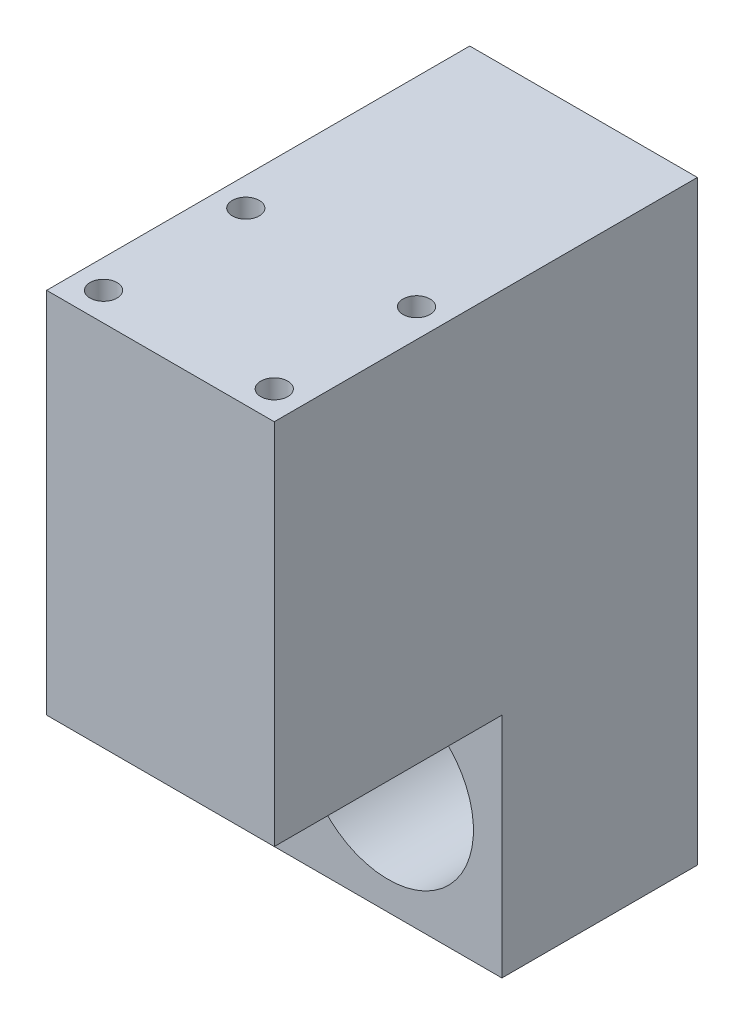
SolidWorks part; units mm, degrees
ref_plane "Front Plane" through (0, 0, 0) normal (0, 0, 1) x (1, 0, 0)
ref_plane "Top Plane" through (0, 0, 0) normal (0, 1, 0) x (1, 0, 0)
ref_plane "Right Plane" through (0, 0, 0) normal (1, 0, 0) x (0, 0, -1)
sketch "Sketch1" plane through (0, 0, 0) normal (0, 1, 0) x (1, 0, 0)
  line L1 (-18.3087, -9.8557) -> (-10.3087, -9.8557)
  line L2 (-18.3087, -9.8557) -> (-18.3087, -2.9857)
  line L3 (-18.3087, -2.9857) -> (-10.3087, -2.9857)
  line L4 (-10.3087, -9.8557) -> (-10.3087, -2.9857)
  dimension "D1" = 6.87
  dimension "D2" = 8
extrude "Boss-Extrude3" add sketch "Sketch1" along normal blind 8
sketch "Sketch2" plane through (0, 8, 0) normal (0, 1, 0) x (1, 0, 0)
  line L1 (-18.3087, -2.9857) -> (-10.3087, -2.9857)
  line L2 (-18.3087, -2.9857) -> (-18.3087, -17.8557)
  line L3 (-18.3087, -17.8557) -> (-10.3087, -17.8557)
  line L4 (-10.3087, -2.9857) -> (-10.3087, -17.8557)
  dimension "D1" = 14.87
  dimension "D2" = 8
extrude "Boss-Extrude5" add sketch "Sketch2" along normal blind 12.93
sketch "Sketch3" plane through (0, 20.93, 0) normal (0, 1, 0) x (1, 0, 0)
  line L0 (-10.3087, -2.9857) -> (-18.3087, -2.9857) construction
  line L1 (-18.3087, -2.9857) -> (-18.3087, -17.8557) construction
  line L2 (-10.3087, -17.8557) -> (-10.3087, -2.9857) construction
  line L3 (-18.3087, -17.8557) -> (-10.3087, -17.8557) construction
  point P0 (-17.3087, -11.8557)
  point P5 (-11.3087, -11.8557)
  point P8 (-11.3087, -16.8557)
  point P11 (-17.3087, -16.8557)
  dimension "D1" = 8.87
  dimension "D2" = 1
  dimension "D3" = 1
  dimension "D4" = 1
  dimension "D5" = 1
hole_wizard "M1.2x0.25 Tapped Hole1" positions "Sketch6" profile "Sketch7" tap size "M1.2x0.25" standard "ANSI Metric" end condition up to next
sketch "Sketch6" plane through (0, 20.93, 0) normal (0, 1, 0) x (1, 0, 0)
  point P5 (-17.3087, -11.8557)
  point P8 (-11.3087, -11.8557)
  point P11 (-17.3087, -16.8557)
  point P14 (-11.3087, -16.8557)
sketch "Sketch7" plane through (-17.3087, 20.93, 11.8557) normal (1, 0, 0) x (0, 0, 1)
  line L0 (0, 0) -> (0, 12.93)
  line L1 (0, 12.93) -> (0.475, 12.93)
  line L2 (0.475, 12.93) -> (0.475, 0)
  line L5 (0.475, 0) -> (0, 0)
  line L11 (0, -6.35) -> (0, 107.95) construction
  dimension "Thru Tap Drill Dia." = 0.95
  dimension "Thru Tap Drill Depth" = 12.93
cosmetic thread "Hole Thread1"
cosmetic thread "Hole Thread2"
cosmetic thread "Hole Thread3"
cosmetic thread "Hole Thread4"
sketch "Sketch8" plane through (0, 0, 2.9857) normal (0, 0, -1) x (-1, 0, 0)
  line L0 (18.3087, 20.93) -> (18.3087, 0) construction
  line L1 (10.3087, 0) -> (18.3087, 0) construction
  point P0 (14.3087, 4)
  dimension "D1" = 4
  dimension "D2" = 4
hole_wizard "Ø1.0mm Dowel Hole1" positions "Sketch8" profile "Sketch10" hole size "Ø1.0" standard "ANSI Metric" end condition up to next
sketch "Sketch10" plane through (-14.3087, 4, 2.9857) normal (1, 0, 0) x (0, 1, 0)
  line L0 (0, 0) -> (0, 6.87)
  line L1 (0, 6.87) -> (3, 6.87)
  line L2 (3, 6.87) -> (3, 0)
  line L5 (3, 0) -> (0, 0)
  line L11 (0, -6.35) -> (0, 107.95) construction
  dimension "Thru Hole Dia." = 6
  dimension "Thru Hole Depth" = 6.87
